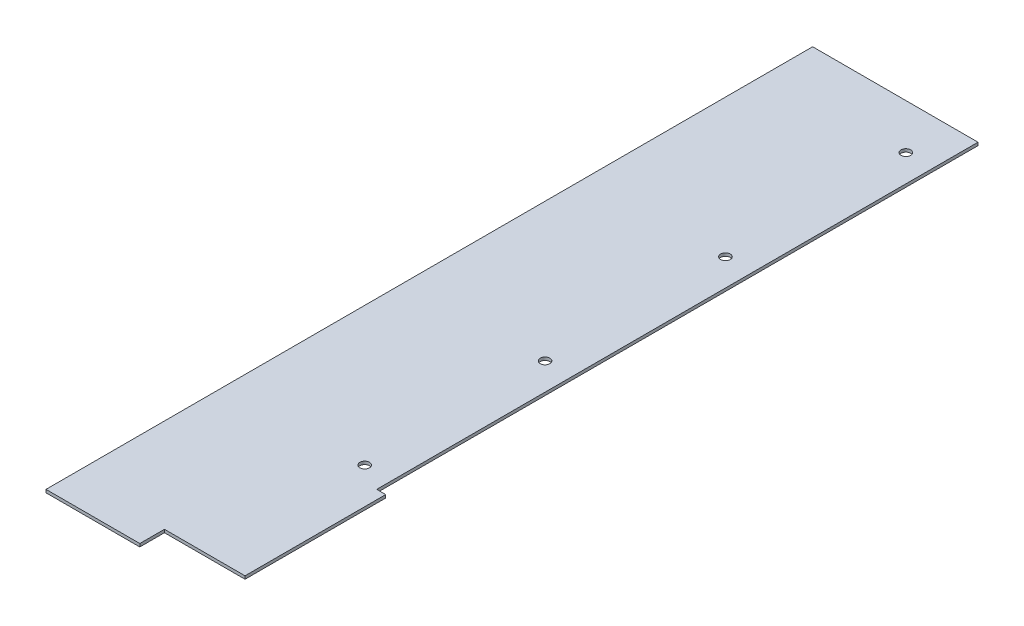
SolidWorks part; units mm, degrees
ref_plane "Plan de face" through (0, 0, 0) normal (0, 0, 1) x (1, 0, 0)
ref_plane "Plan de dessus" through (0, 0, 0) normal (0, 1, 0) x (1, 0, 0)
ref_plane "Plan de droite" through (0, 0, 0) normal (1, 0, 0) x (0, 0, -1)
sketch "Esquisse1" plane through (0, 0, 0) normal (0, 1, 0) x (1, 0, 0)
  line L0 (0, 0) -> (0, 255)
  line L1 (0, 255) -> (55, 255)
  line L2 (55, 255) -> (55, 55)
  line L3 (0, 0) -> (31.2, 0)
  line L4 (55, 55) -> (58, 55)
  line L5 (58, 55) -> (58, 8.2)
  line L6 (58, 8.2) -> (55, 8.2)
  line L7 (31.2, 0) -> (31.2, 8.2)
  line L8 (31.2, 8.2) -> (55, 8.2)
  circle A0 centre (46, 60) radius 1.6
  circle A1 centre (46, 120) radius 1.6
  circle A2 centre (46, 180) radius 1.6
  circle A3 centre (46, 240) radius 1.6
  dimension "D4" = 3.2
  dimension "D1" = 255
  dimension "D2" = 55
  dimension "D3" = 9
  dimension "D5" = 31.2
  dimension "D7" = 8.2
  dimension "D8" = 3
  dimension "D9" = 60
  dimension "D10" = 55
  dimension "D6" = 4
extrude "Boss.-Extru.1" add sketch "Esquisse1" along normal blind 1
